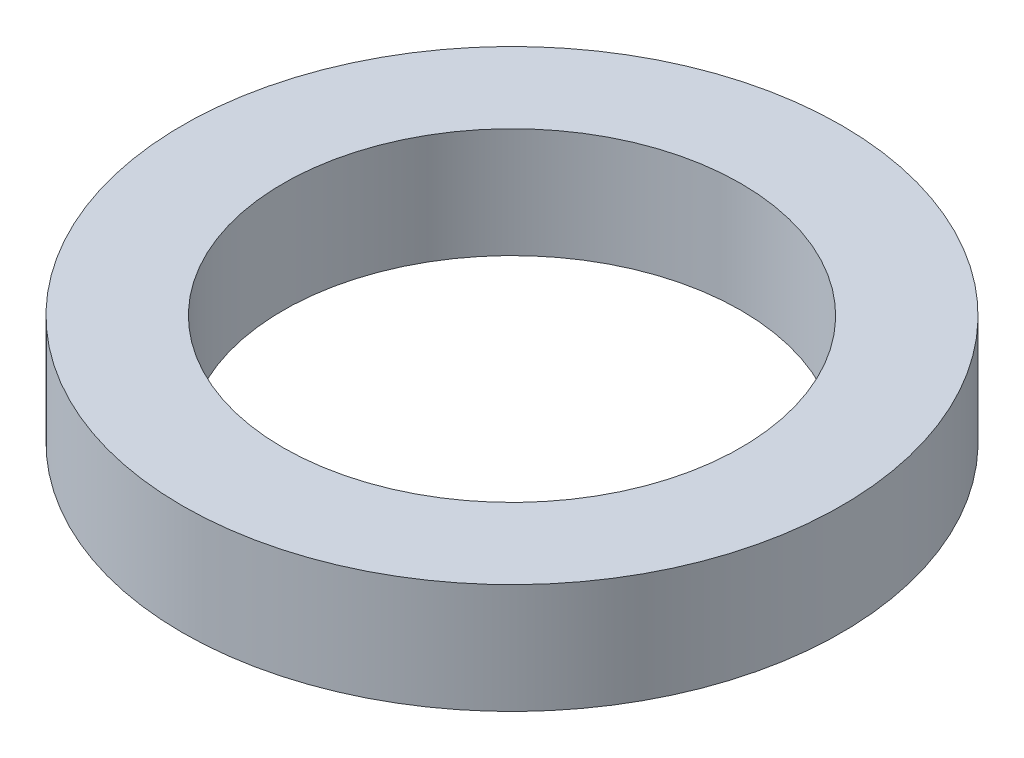
SolidWorks part; units mm, degrees
ref_plane "Front Plane" through (0, 0, 0) normal (0, 0, 1) x (1, 0, 0)
ref_plane "Top Plane" through (0, 0, 0) normal (0, 1, 0) x (1, 0, 0)
ref_plane "Right Plane" through (0, 0, 0) normal (1, 0, 0) x (0, 0, -1)
sketch "Sketch1" plane through (0, 0, 0) normal (0, 1, 0) x (1, 0, 0)
  circle A0 centre (0, 0) radius 9
  circle A1 centre (0, 0) radius 6.25
  dimension "D1" = 18
  dimension "D2" = 12.5
extrude "Boss-Extrude1" add sketch "Sketch1" along normal blind 3
